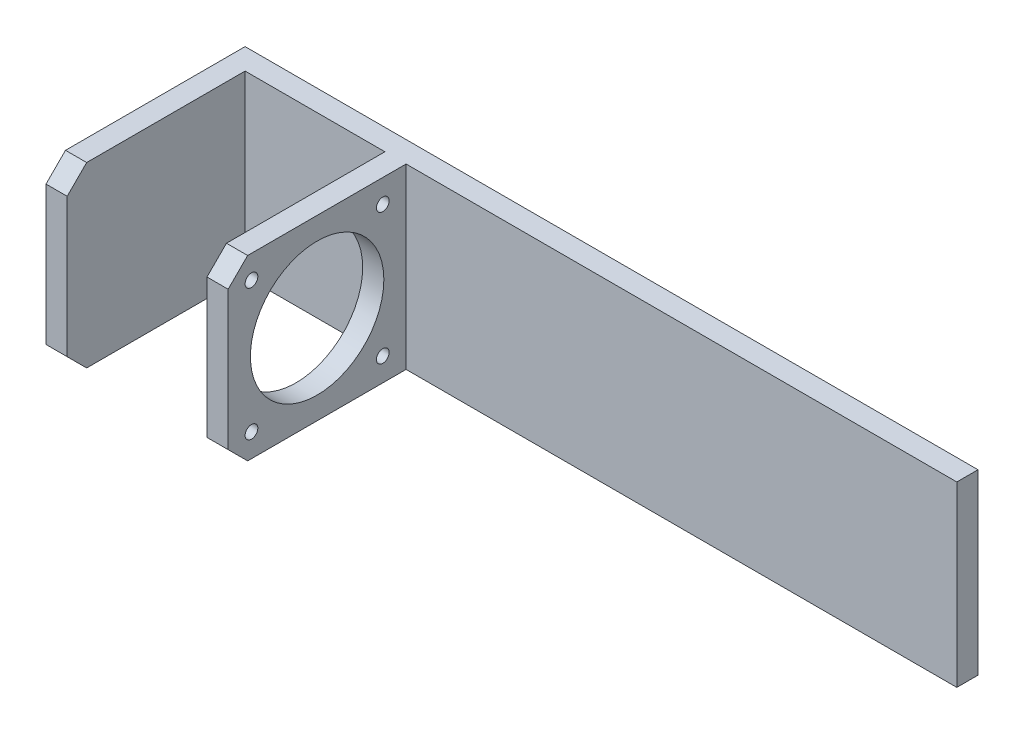
SolidWorks part; units mm, degrees
ref_plane "Front Plane" through (0, 0, 0) normal (0, 0, 1) x (1, 0, 0)
ref_plane "Top Plane" through (0, 0, 0) normal (0, 1, 0) x (1, 0, 0)
ref_plane "Right Plane" through (0, 0, 0) normal (1, 0, 0) x (0, 0, -1)
sketch "Sketch2" plane through (0, 0, 0) normal (1, 0, 0) x (0, 0, -1)
  line L0 (-21, 16.4) -> (-21, -16.4)
  line L1 (-21, -16.4) -> (-16.4, -21)
  line L2 (-16.4, -21) -> (16.4, -21)
  line L3 (16.4, -21) -> (21, -16.4)
  line L4 (21, -16.4) -> (21, 16.4)
  line L5 (21, 16.4) -> (16.4, 21)
  line L6 (16.4, 21) -> (-16.4, 21)
  line L7 (-16.4, 21) -> (-21, 16.4)
  arc A0 (-14, 15.5) -> (-17, 15.5) centre (-15.5, 15.5) ccw
  arc A1 (-17, 15.5) -> (-14, 15.5) centre (-15.5, 15.5) ccw
  arc A2 (15.75, 0) -> (-15.75, 0) centre (0, 0) ccw
  arc A3 (-15.75, 0) -> (15.75, 0) centre (0, 0) ccw
  arc A4 (17, -15.5) -> (14, -15.5) centre (15.5, -15.5) ccw
  arc A5 (14, -15.5) -> (17, -15.5) centre (15.5, -15.5) ccw
  arc A6 (17, 15.5) -> (14, 15.5) centre (15.5, 15.5) ccw
  arc A7 (14, 15.5) -> (17, 15.5) centre (15.5, 15.5) ccw
  arc A8 (-14, -15.5) -> (-17, -15.5) centre (-15.5, -15.5) ccw
  arc A9 (-17, -15.5) -> (-14, -15.5) centre (-15.5, -15.5) ccw
extrude "Boss-Extrude1" add sketch "Sketch2" along normal blind 5
sketch "Sketch4" plane through (5, 0, 0) normal (1, 0, 0) x (0, 0, -1)
  line L1 (16.4, 21) -> (26, 21)
  line L2 (16.4, 21) -> (16.4, -21)
  line L3 (16.4, -21) -> (26, -21)
  line L4 (26, 21) -> (26, -21)
  line L12 (-16.4, 21) -> (-21, 16.4)
  line L13 (-21, 16.4) -> (-21, -16.4)
  line L14 (-21, -16.4) -> (-16.4, -21)
  line L15 (-16.4, -21) -> (16.4, -21)
  line L16 (16.4, -21) -> (21, -16.4)
  line L17 (21, -16.4) -> (21, 16.4)
  line L18 (21, 16.4) -> (16.4, 21)
  line L19 (16.4, 21) -> (-16.4, 21)
  line L20 (-16.4, 21) -> (-21, 16.4)
  line L21 (-21, 16.4) -> (-21, -16.4)
  line L22 (-21, -16.4) -> (-16.4, -21)
  line L23 (-16.4, -21) -> (16.4, -21)
  line L24 (16.4, -21) -> (21, -16.4)
  line L25 (21, -16.4) -> (21, 16.4)
  line L26 (21, 16.4) -> (16.4, 21)
  line L27 (16.4, 21) -> (-16.4, 21)
  line M17 (16.4, -21) -> (21, -16.4)
  line M18 (21, -16.4) -> (21, 16.4)
  line M19 (21, 16.4) -> (16.4, 21)
  dimension "D1" = 0
extrude "Boss-Extrude3" add sketch "Sketch4" against normal blind 5 contours L4 L1 L3 M19 M18 M17
sketch "Sketch5" plane through (0, 0, 0) normal (-1, 0, 0) x (0, 0, 1)
  line L0 (16.4, -21) -> (-26, -21) construction
  line L1 (-26, 21) -> (-21, 21)
  line L2 (-26, 21) -> (-26, -21)
  line L3 (-26, -21) -> (-21, -21)
  line L4 (-21, 21) -> (-21, -21)
extrude "Boss-Extrude4" add sketch "Sketch5" along normal blind 33
sketch "Sketch6" plane through (-33, 0, 0) normal (-1, 0, 0) x (0, 0, 1)
  line L10 (-26, 21) -> (-26, -21)
  line L11 (-26, -21) -> (-21, -21)
  line L12 (-21, 21) -> (-21, -21)
  line L13 (-21, -21) -> (16.4, -21)
  line L14 (16.4, -21) -> (21, -16.4)
  line L15 (21, -16.4) -> (21, 16.4)
  line L16 (21, 16.4) -> (16.4, 21)
  line L17 (16.4, 21) -> (-21, 21)
  line L18 (-21, 21) -> (-21, -21)
  line L19 (-21, -21) -> (16.4, -21)
  line L20 (16.4, -21) -> (21, -16.4)
  line L21 (21, -16.4) -> (21, 16.4)
  line L22 (21, 16.4) -> (16.4, 21)
  line L23 (16.4, 21) -> (-21, 21)
  line L24 (-21, -21) -> (-21, 21)
  line L25 (-21, 21) -> (-26, 21)
  line L26 (-26, 21) -> (-26, -21)
  line L27 (-26, -21) -> (-21, -21)
  line L28 (-21, -21) -> (-21, 21)
  line L29 (-21, 21) -> (-26, 21)
  line M11 (-26, 21) -> (-26, -21)
  line M12 (-26, -21) -> (-21, -21)
  line M13 (-21, -21) -> (-21, 21)
  line M14 (-21, 21) -> (-26, 21)
  dimension "D1" = 0
  dimension "D2" = 0
extrude "Boss-Extrude5" add sketch "Sketch6" along normal blind 5 contours M14 M11 M12 M13 | L22 L23 L19 L20 L21 M13
sketch "Sketch7" plane through (5, 0, 0) normal (1, 0, 0) x (0, 0, -1)
  line L0 (-16.4, -21) -> (26, -21) construction
  line L1 (26, 21) -> (21, 21)
  line L2 (26, 21) -> (26, -21)
  line L3 (26, -21) -> (21, -21)
  line L4 (21, 21) -> (21, -21)
extrude "Boss-Extrude6" add sketch "Sketch7" along normal blind 130
